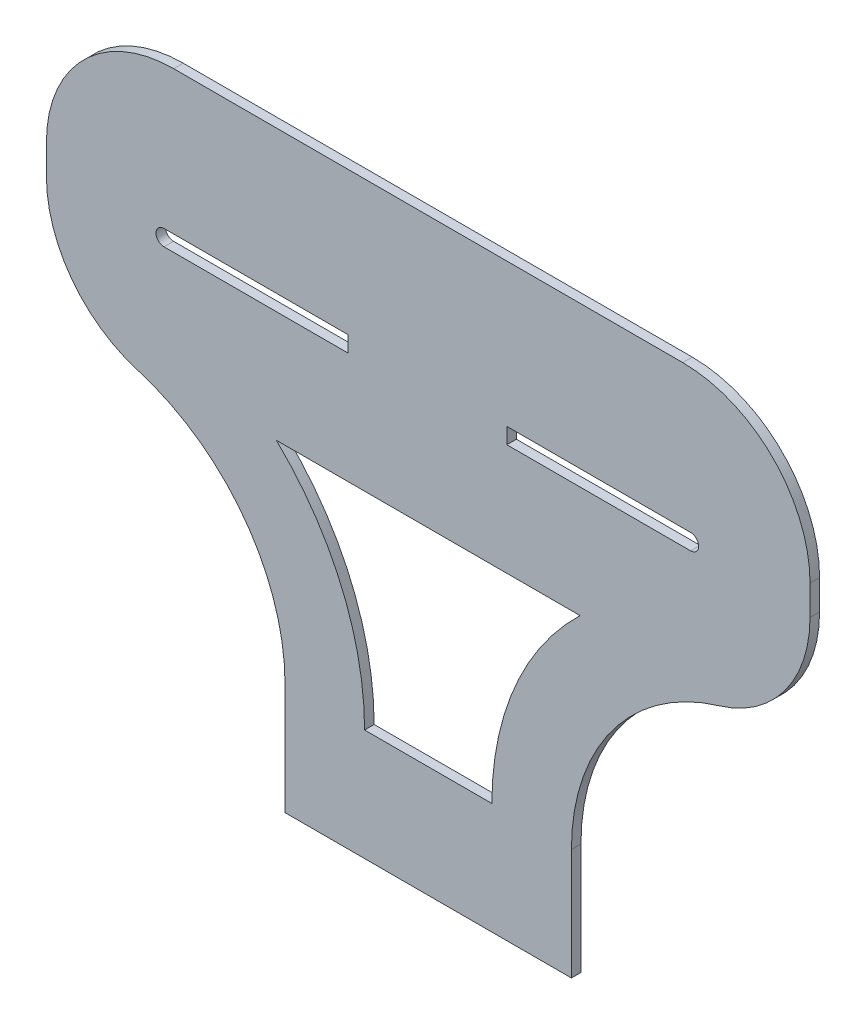
SolidWorks part; units mm, degrees
ref_plane "Plano frontal" through (0, 0, 0) normal (0, 0, 1) x (1, 0, 0)
ref_plane "Plano superior" through (0, 0, 0) normal (0, 1, 0) x (1, 0, 0)
ref_plane "Plano direito" through (0, 0, 0) normal (1, 0, 0) x (0, 0, -1)
sketch "Esboço1" plane through (0, 0, 0) normal (0, 0, 1) x (1, 0, 0)
  line L0 (0, 70) -> (-150, 70)
  line L1 (0, 0) -> (180, 0)
  line L2 (0, 0) -> (0, 70)
  line L3 (-150, 70) -> (-150, 200)
  line L4 (180, 0) -> (180, 70)
  line L5 (-150, 70) -> (0, 70)
  line L6 (180, 70) -> (330, 70)
  line L7 (-150, 200) -> (330, 200) construction
  line L8 (330, 200) -> (330, 70)
  line L9 (-150, 200) -> (-150, 370)
  line L10 (-150, 370) -> (330, 370)
  line L11 (330, 370) -> (330, 200)
  dimension "D1" = 480
  dimension "D2" = 180
  dimension "D3" = 70
  dimension "D4" = 130
  dimension "D5" = 170
extrude "Ressalto-extrusão1" add sketch "Esboço1" along normal blind 6
sketch "Esboço3" plane through (0, 0, 0) normal (0, 0, 1) x (1, 0, 0)
  line L0 (0, 70) -> (-150, 70)
  line L1 (0, 0) -> (180, 0)
  line L2 (0, 0) -> (0, 70)
  line L3 (-150, 70) -> (-150, 200)
  line L4 (180, 0) -> (180, 70)
  line L5 (-150, 70) -> (0, 70)
  line L6 (180, 70) -> (330, 70)
  line L7 (-150, 200) -> (330, 200) construction
  line L8 (330, 200) -> (330, 70)
  line L9 (-150, 200) -> (-150, 350)
  line L10 (-150, 350) -> (330, 350)
  line L11 (330, 350) -> (330, 200)
  line L13 (254.974, 280) -> (-76.1202, 280)
  line L14 (254.974, 270) -> (-76.1202, 270)
  circle A0 centre (-76.1202, 275) radius 75
  circle A1 centre (254.974, 275) radius 75
  arc A2 (-76.1202, 280) -> (-76.1202, 270) centre (-76.1202, 275) ccw
  arc A3 (254.974, 280) -> (254.974, 270) centre (254.974, 275) cw
  dimension "D6" = 150
  dimension "D1" = 480
  dimension "D2" = 180
  dimension "D3" = 70
  dimension "D4" = 130
  dimension "D5" = 150
fillet "Filete1" radius 80 2 edges at (330, 370, 3) (-150, 370, 3)
sketch "Esboço4" plane through (0, 0, 6) normal (0, 0, 1) x (1, 0, 0)
  line L0 (-150, 70) -> (0, 70)
  line L1 (-150, 200) -> (330, 200) construction
  line L2 (-126.1352, 200) -> (-150, 200)
  line L3 (-150, 200) -> (-150, 70)
  line L4 (330, 200) -> (306.1352, 200)
  line L5 (330, 200) -> (330, 70)
  line L6 (180, 70) -> (330, 70)
  line L9 (180, 70) -> (330, 70) construction
  arc A0 (0, 70) -> (-126.1352, 200) centre (-130.0592, 70) ccw
  arc A2 (180, 70) -> (306.1352, 200) centre (310.0592, 70) cw
extrude "Corte-extrusão1" cut sketch "Esboço4" against normal through all
fillet "Filete2" radius 80 2 edges at (330, 200, 3) (-150, 200, 3)
sketch "Esboço5" plane through (0, 0, 6) normal (0, 0, 1) x (1, 0, 0)
  line L0 (254.974, 280) -> (-76.1202, 280) construction
  line L1 (254.974, 270) -> (-76.1202, 270) construction
  line L2 (254.974, 280) -> (-76.1202, 280)
  line L3 (254.974, 270) -> (-76.1202, 270)
  arc A0 (-76.1202, 280) -> (-76.1202, 270) centre (-76.1202, 275) ccw construction
  arc A1 (254.974, 270) -> (254.974, 280) centre (254.974, 275) ccw construction
  arc A2 (-76.1202, 280) -> (-76.1202, 270) centre (-76.1202, 275) ccw
  arc A3 (254.974, 270) -> (254.974, 280) centre (254.974, 275) ccw
extrude "Corte-extrusão2" cut sketch "Esboço5" against normal through all
sketch "Esboço6" plane through (0, 0, 6) normal (0, 0, 1) x (1, 0, 0)
  line L3 (90, 0) -> (90, 70) construction
  line L4 (0, 0) -> (180, 0) construction
  line L5 (50, 70) -> (130, 70.0203)
  line L6 (-150, 200) -> (330, 200) construction
  line L7 (-5.4746, 200) -> (185.4534, 200) construction
  line L8 (-5.4746, 200) -> (185.4534, 200)
  arc A4 (50, 70) -> (-5.4746, 200) centre (-130.0592, 70) ccw
  arc A5 (185.4534, 200) -> (130, 70.0203) centre (310.0592, 70.0203) ccw
extrude "Corte-extrusão3" cut sketch "Esboço6" against normal blind 6
sketch "Esboço7" plane through (0, 0, 6) normal (0, 0, 1) x (1, 0, 0)
  line L0 (254.974, 270) -> (-76.1202, 270) construction
  line L1 (254.974, 280) -> (-76.1202, 280) construction
  line L2 (139.4269, 270) -> (39.4269, 270)
  line L3 (139.4269, 280) -> (39.4269, 280)
  line L5 (39.4269, 280) -> (39.4269, 270)
  line L6 (139.4269, 280) -> (139.4269, 270)
  line L9 (330, 271.2902) -> (330, 290)
  line L10 (250, 370) -> (-70, 370)
  line L11 (-150, 290) -> (-150, 271.2902)
  line L12 (0, 70) -> (0, 0)
  line L13 (0, 0) -> (180, 0)
  line L14 (180, 0) -> (180, 70)
  arc A6 (272.8732, 194.6299) -> (180, 70) centre (310.0592, 70) ccw
  arc A7 (272.8732, 194.6299) -> (330, 271.2902) centre (250, 271.2902) ccw
  arc A8 (330, 290) -> (250, 370) centre (250, 290) ccw
  arc A9 (-70, 370) -> (-150, 290) centre (-70, 290) ccw
  arc A10 (-150, 271.2902) -> (-92.8732, 194.6299) centre (-70, 271.2902) ccw
  arc A11 (0, 70) -> (-92.8732, 194.6299) centre (-130.0592, 70) ccw
  dimension "D1" = 0
extrude "Ressalto-extrusão4" add sketch "Esboço7" against normal blind 6 contours L5 L2 L6 L3
